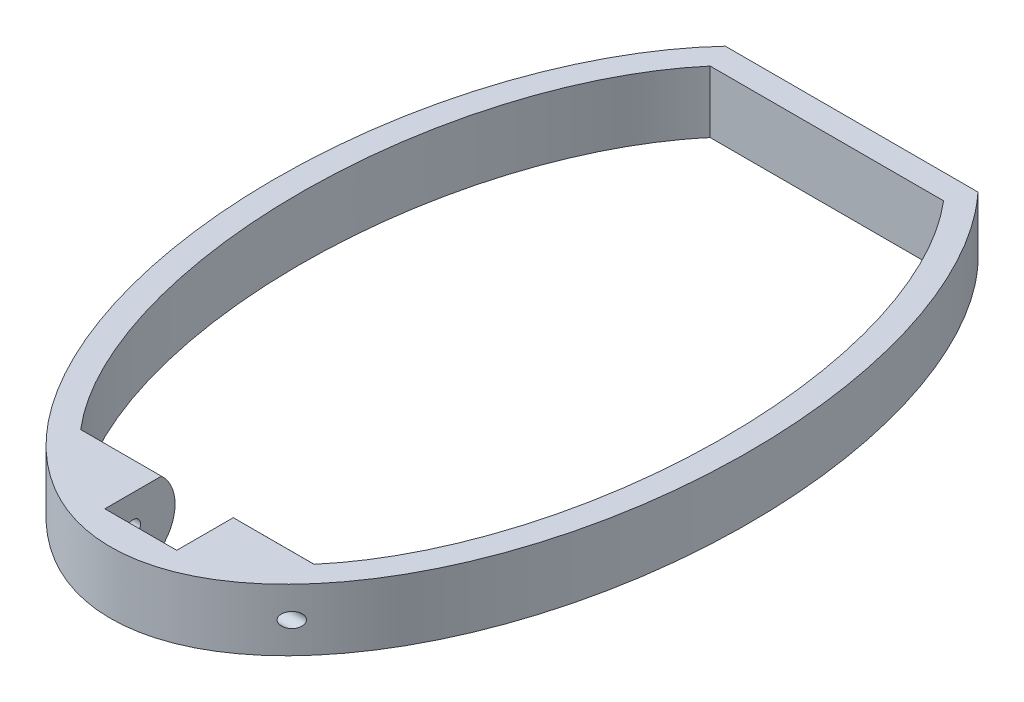
SolidWorks part; units mm, degrees
ref_plane "Front Plane" through (0, 0, 0) normal (0, 0, 1) x (1, 0, 0)
ref_plane "Top Plane" through (0, 0, 0) normal (0, 1, 0) x (1, 0, 0)
ref_plane "Right Plane" through (0, 0, 0) normal (1, 0, 0) x (0, 0, -1)
sketch "Sketch1" plane through (0, 0, 0) normal (0, 1, 0) x (1, 0, 0)
  line L0 (0, 0) -> (0, 58.7756) construction
  line L1 (0, 0) -> (13.1013, 0) construction
  ellipse E0 centre (0, 0) end of major axis (0, 38.1) minor radius 21.209
  dimension "D1" = 42.418
  dimension "D2" = 76.2
extrude "Boss-Extrude1" [suppressed] add sketch "Sketch1" along normal blind 6.35
sketch "Sketch7" [suppressed] plane through (0, 6.35, 0) normal (0, 1, 0) x (1, 0, 0)
  line L0 (-11.7237, 31.75) -> (11.7237, 31.75)
  ellipse E0 centre (0, 0) end of major axis (0, 38.1) minor radius 21.209 construction
  ellipse E1 centre (0, 0) end of major axis (0, 38.1) minor radius 21.209 (11.7237, 31.75) -> (-11.7237, 31.75) ccw
  dimension "D1" = 31.75
extrude "Cut-Extrude6" [suppressed] cut sketch "Sketch7" against normal through all
sketch "Sketch35" [suppressed] plane through (0, 6.35, 0) normal (0, 1, 0) x (1, 0, 0)
  line L0 (0, -11.1645) -> (0, -20.2039) construction
  line L2 (3.175, -38.1) -> (21.209, -38.1)
  line L3 (3.175, -38.1) -> (3.175, -31.75)
  line L4 (3.175, -31.75) -> (21.209, -31.75)
  line L5 (21.209, -38.1) -> (21.209, -31.75)
  line L6 (-3.175, -31.75) -> (-21.209, -31.75)
  line L7 (-3.175, -31.75) -> (-3.175, -38.1)
  line L8 (-3.175, -38.1) -> (-21.209, -38.1)
  line L9 (-21.209, -31.75) -> (-21.209, -38.1)
  ellipse E0 centre (0, 0) end of major axis (0, 38.1) minor radius 21.209 (-11.7237, 31.75) -> (11.7237, 31.75) ccw construction
  dimension "D1" = 6.35
  dimension "D2" = 6.35
extrude "Cut-Extrude17" [suppressed] cut sketch "Sketch35" against normal through all
sketch "Sketch36" plane through (0, 0, 0) normal (0, 1, 0) x (1, 0, 0)
  line L7 (-12.9456, 34.798) -> (12.9459, 34.798)
  line L15 (-3.683, -32.258) -> (-3.683, -38.053)
  line L16 (3.683, -38.053) -> (3.683, -32.258)
  line L17 (3.683, -32.258) -> (11.9592, -32.258)
  line L18 (11.9592, 32.258) -> (-11.9592, 32.258)
  line L19 (-11.9592, -32.258) -> (-3.683, -32.258)
  ellipse E4 centre (0, 0) end of major axis (0.0002, 41.148) minor radius 24.257 (-12.9456, 34.798) -> (12.9459, 34.798) ccw
  spline S3 degree 3 poles (-3.683, -38.053) (-2.4821, -38.4177) (-1.2584, -38.607) (0.3018, -38.6083) (0.6164, -38.5965) (1.2403, -38.5494) (1.5503, -38.5142) (2.4742, -38.3742) (3.0823, -38.2354) (3.683, -38.053) knots 0 0 0 0 0.5 0.5 0.625 0.625 0.75 0.75 1 1 1 1
  spline S4 degree 3 poles (11.9592, -32.258) (12.9008, -31.1565) (13.7385, -29.9921) (15.2594, -27.5703) (15.9419, -26.3123) (16.87, -24.3676) (17.1639, -23.7081) (17.7185, -22.3785) (17.9789, -21.7097) (18.7139, -19.6919) (19.1428, -18.3319) (20.2712, -14.2135) (20.8143, -11.4172) (21.3579, -7.1571) (21.4934, -5.7221) (21.6726, -2.8617) (21.7168, -1.4337) (21.7173, 2.8439) (21.543, 5.6872) (21.0042, 9.9388) (20.7778, 11.3544) (20.2237, 14.1779) (19.8984, 15.5736) (19.1435, 18.33) (18.7141, 19.6908) (17.7373, 22.3731) (17.1901, 23.6946) (16.2627, 25.6412) (15.9349, 26.2855) (15.245, 27.5494) (14.8827, 28.1699) (13.738, 29.9933) (12.8989, 31.1588) (11.9592, 32.258) knots 0 0 0 0 0.0625 0.0625 0.125 0.125 0.15625 0.15625 0.1875 0.1875 0.25 0.25 0.375 0.375 0.4375 0.4375 0.5 0.5 0.625 0.625 0.6875 0.6875 0.75 0.75 0.8125 0.8125 0.875 0.875 0.90625 0.90625 0.9375 0.9375 1 1 1 1
  spline S5 degree 3 poles (-11.9592, 32.258) (-12.9008, 31.1565) (-13.7385, 29.9921) (-15.2594, 27.5703) (-15.9419, 26.3123) (-16.87, 24.3676) (-17.1639, 23.7081) (-17.7185, 22.3785) (-17.9789, 21.7097) (-18.7139, 19.6919) (-19.1428, 18.3319) (-20.2712, 14.2135) (-20.8143, 11.4172) (-21.3579, 7.1571) (-21.4934, 5.7221) (-21.6726, 2.8617) (-21.7168, 1.4337) (-21.7173, -2.8439) (-21.543, -5.6872) (-21.0042, -9.9388) (-20.7778, -11.3544) (-20.2237, -14.1779) (-19.8984, -15.5736) (-19.1435, -18.33) (-18.7141, -19.6908) (-17.7373, -22.3731) (-17.1901, -23.6946) (-16.2627, -25.6412) (-15.9349, -26.2855) (-15.245, -27.5494) (-14.8827, -28.1699) (-13.738, -29.9933) (-12.8989, -31.1588) (-11.9592, -32.258) knots 0 0 0 0 0.0625 0.0625 0.125 0.125 0.15625 0.15625 0.1875 0.1875 0.25 0.25 0.375 0.375 0.4375 0.4375 0.5 0.5 0.625 0.625 0.6875 0.6875 0.75 0.75 0.8125 0.8125 0.875 0.875 0.90625 0.90625 0.9375 0.9375 1 1 1 1
  dimension "D2" = 2.54
extrude "Boss-Extrude2" add sketch "Sketch36" along normal blind 6.35 separate body
sketch "Sketch37" plane through (0, 0, 0) normal (1, 0, 0) x (0, 0, -1)
  line L0 (-38.053, 0) -> (-32.258, 6.35) construction
  circle A0 centre (-35.1555, 3.175) radius 0.762
  point P4 (-35.1555, 3.175)
  dimension "D1" = 1.524
extrude "Cut-Extrude18" cut sketch "Sketch37" against normal through all both and the other way through all
sketch "Sketch40" plane through (3.683, 0, 0) normal (-1, 0, 0) x (0, 0, 1)
  line L0 (32.258, 0) -> (32.258, 6.35)
  arc A0 (32.258, 6.35) -> (32.258, 0) centre (35.1555, 3.175) ccw
extrude "Boss-Extrude3" add sketch "Sketch40" against normal up to surface (8.2762 mm away) up to face at (11.9592, 4.7625, 16.129)
sketch "Sketch41" plane through (-3.683, 0, 0) normal (1, 0, 0) x (0, 0, -1)
  line L0 (-32.258, 0) -> (-32.258, 6.35)
  arc A0 (-32.258, 0) -> (-32.258, 6.35) centre (-35.1555, 3.175) ccw
extrude "Boss-Extrude4" add sketch "Sketch41" against normal up to surface (8.2762 mm away) up to face at (-11.9592, 4.7625, -16.129)
sketch "Sketch42" plane through (3.683, 0, 0) normal (-1, 0, 0) x (0, 0, 1)
  line L0 (38.053, 0) -> (32.258, 0) construction
  line L1 (38.053, 6.35) -> (39.7491, 6.35)
  line L2 (38.053, 6.35) -> (38.053, 0)
  line L3 (38.053, 0) -> (39.7491, 0)
  line L4 (39.7491, 6.35) -> (39.7491, 0)
extrude "Boss-Extrude5" add sketch "Sketch42" along normal up to surface (7.366 mm away) up to face at (-3.683, 3.175, 34.3935)
sketch "Sketch43" plane through (3.683, 0, 0) normal (-1, 0, 0) x (0, 0, 1)
  circle A0 centre (35.1555, 3.175) radius 4.2984
extrude "Cut-Extrude19" cut sketch "Sketch43" along normal up to surface (7.366 mm away) up to face at (-3.683, 3.175, 34.3935)
